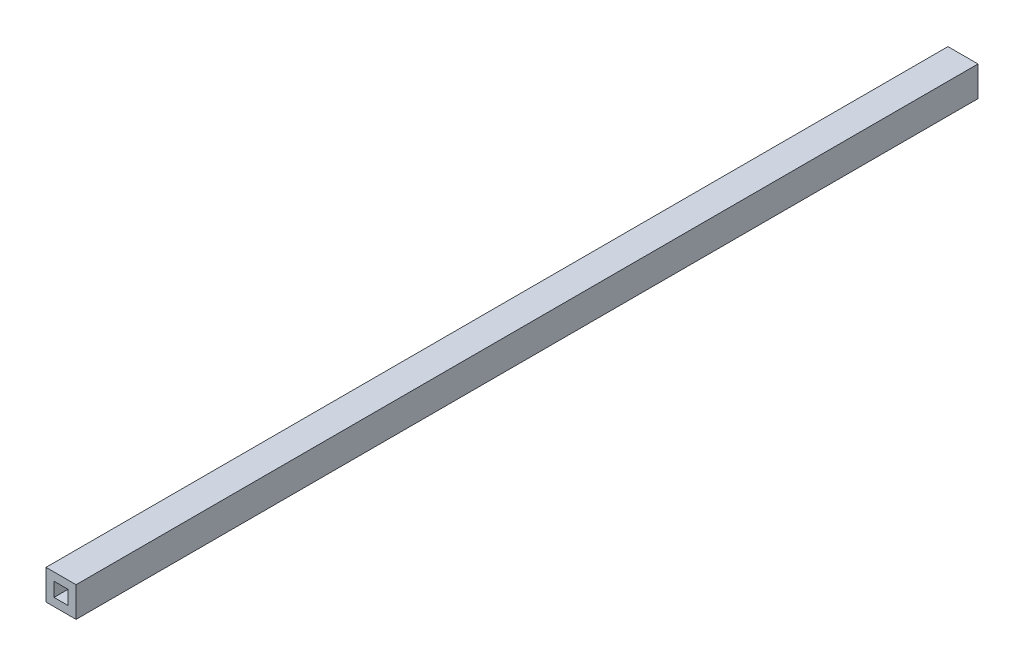
SolidWorks part; units mm, degrees
ref_plane "Front Plane" through (0, 0, 0) normal (0, 0, 1) x (1, 0, 0)
ref_plane "Top Plane" through (0, 0, 0) normal (0, 1, 0) x (1, 0, 0)
ref_plane "Right Plane" through (0, 0, 0) normal (1, 0, 0) x (0, 0, -1)
sketch "Sketch1" plane through (0, 0, 0) normal (0, 0, 1) x (1, 0, 0)
  line L1 (-5.9447, 3.4452) -> (13.1053, 3.4452)
  line L2 (-5.9447, 3.4452) -> (-5.9447, -15.6048)
  line L3 (-5.9447, -15.6048) -> (13.1053, -15.6048)
  line L4 (13.1053, 3.4452) -> (13.1053, -15.6048)
  line L5 (-0.8647, -1.6348) -> (8.0253, -1.6348)
  line L6 (-0.8647, -1.6348) -> (-0.8647, -10.5248)
  line L7 (-0.8647, -10.5248) -> (8.0253, -10.5248)
  line L8 (8.0253, -1.6348) -> (8.0253, -10.5248)
  point P8 (3.5803, -1.6348)
  point P9 (3.5803, -15.6048)
  point P10 (-5.9447, -6.0798)
  dimension "D1" = 19.05
  dimension "D2" = 19.05
  dimension "D3" = 5.08
  dimension "D4" = 5.08
  dimension "D5" = 5.08
  dimension "D6" = 5.08
extrude "Boss-Extrude1" add sketch "Sketch1" along normal blind 571.5
